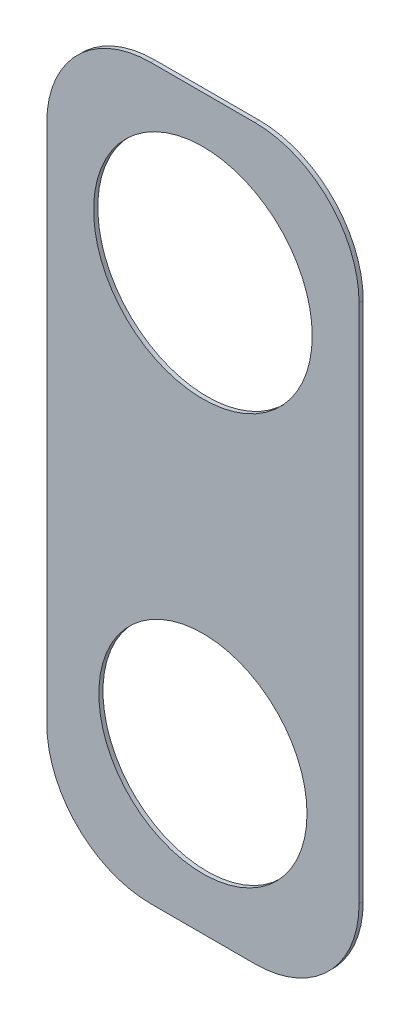
SolidWorks part; units mm, degrees
ref_plane "Front Plane" through (0, 0, 0) normal (0, 0, 1) x (1, 0, 0)
ref_plane "Top Plane" through (0, 0, 0) normal (0, 1, 0) x (1, 0, 0)
ref_plane "Right Plane" through (0, 0, 0) normal (1, 0, 0) x (0, 0, -1)
sketch "Sketch2" plane through (0, 0, 0) normal (0, 0, 1) x (1, 0, 0)
  line L0 (19.05, 88.9) -> (19.05, 0) construction
  line L1 (12.7, 0) -> (25.4, 0)
  line L2 (0, 12.7) -> (0, 76.2)
  line L3 (12.7, 88.9) -> (25.4, 88.9)
  line L4 (38.1, 12.7) -> (38.1, 76.2)
  line L5 (0, 19.05) -> (38.1, 19.05) construction
  line L6 (0, 69.85) -> (38.1, 69.85) construction
  arc A0 (0, 12.7) -> (12.7, 0) centre (12.7, 12.7) ccw
  arc A1 (25.4, 0) -> (38.1, 12.7) centre (25.4, 12.7) ccw
  arc A2 (38.1, 76.2) -> (25.4, 88.9) centre (25.4, 76.2) ccw
  arc A3 (12.7, 88.9) -> (0, 76.2) centre (12.7, 76.2) ccw
  circle A4 centre (19.05, 69.85) radius 13.335
  circle A5 centre (19.05, 19.05) radius 12.7
  point P7 (0, 0)
  point P10 (38.1, 0)
  point P13 (38.1, 88.9)
  point P16 (0, 88.9)
  dimension "D3" = 12.7
  dimension "D6" = 26.67
  dimension "D7" = 25.4
  dimension "D1" = 88.9
  dimension "D2" = 38.1
  dimension "D4" = 19.05
  dimension "D5" = 19.05
extrude "Boss-Extrude1" add sketch "Sketch2" along normal blind 0.508
equation "\"F\"= 650"
equation "\"Sy\"= 36000"
equation "\"stress\"= 9000"
equation "\"E\"= 29 * 10 ^ 6"
equation "\"deflection\"= 0.005"
equation "\"w\"= 0.02"
equation "\"h\"= 3.5"
equation "\"d_shaft\"= 1"
equation "\"d_part\"= 1.05"
